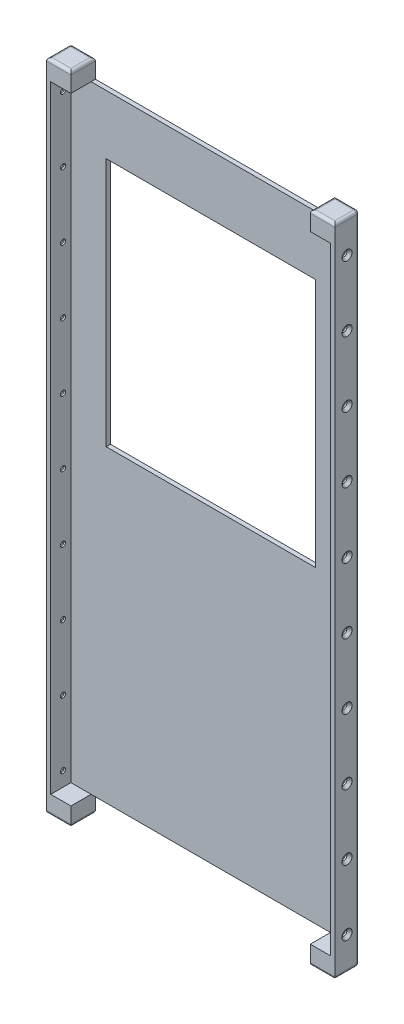
SolidWorks part; units mm, degrees
ref_plane "Front Plane" through (0, 0, 0) normal (0, 0, 1) x (1, 0, 0)
ref_plane "Top Plane" through (0, 0, 0) normal (0, 1, 0) x (1, 0, 0)
ref_plane "Right Plane" through (0, 0, 0) normal (1, 0, 0) x (0, 0, -1)
sketch "Sketch1" plane through (0, 0, 0) normal (0, 0, 1) x (1, 0, 0)
  line L0 (0, 107) -> (0, -107) construction
  line L1 (-41.5, -107) -> (41.5, -107)
  line L2 (-50, -107) -> (-50, 107)
  line L3 (-41.5, 107) -> (41.5, 107)
  line L4 (50, -107) -> (50, 107)
  line L5 (-50, -107) -> (50, 107) construction
  line L6 (-50, 107) -> (50, -107) construction
  line L7 (-50, 0) -> (50, 0) construction
  line L8 (-50, 107) -> (-50, 113.5)
  line L9 (-50, 113.5) -> (-41.5, 113.5)
  line L10 (-41.5, 107) -> (-41.5, 113.5)
  line L12 (50, 107) -> (50, 113.5)
  line L13 (50, 113.5) -> (41.5, 113.5)
  line L14 (41.5, 107) -> (41.5, 113.5)
  line L16 (50, -107) -> (50, -113.5)
  line L17 (50, -113.5) -> (41.5, -113.5)
  line L18 (41.5, -107) -> (41.5, -113.5)
  line L20 (-50, -107) -> (-50, -113.5)
  line L21 (-50, -113.5) -> (-41.5, -113.5)
  line L22 (-41.5, -107) -> (-41.5, -113.5)
  point P0 (0, 0)
  dimension "D1" = 100
  dimension "D2" = 227
  dimension "D3" = 8.5
  dimension "D4" = 6.5
extrude "Boss-Extrude1" add sketch "Sketch1" along normal blind 8.5
fillet "Fillet1" radius 1 18 edges at (41.5, -113.5, 4.25) (45.75, -113.5, 8.5) (50, -113.5, 4.25) (45.75, -113.5, 0) (-50, -113.5, 4.25) (-45.75, -113.5, 8.5) (-41.5, -113.5, 4.25) (-45.75, -113.5, 0) (-41.5, 113.5, 4.25) (-45.75, 113.5, 8.5) (-50, 113.5, 4.25) (-45.75, 113.5, 0) (41.5, 113.5, 4.25) (45.75, 113.5, 8.5) (50, 113.5, 4.25) (45.75, 113.5, 0) (-50, 0, 0) (50, 0, 0)
sketch "Sketch2" plane through (0, 0, 8.5) normal (0, 0, 1) x (1, 0, 0)
  line L1 (-41.5, 107) -> (41.5, 107)
  line L2 (-41.5, 107) -> (-41.5, -107)
  line L3 (-41.5, -107) -> (41.5, -107)
  line L4 (41.5, 107) -> (41.5, -107)
extrude "Cut-Extrude1" cut sketch "Sketch2" against normal blind 7
sketch "Sketch3" plane through (0, 0, 8.5) normal (0, 0, 1) x (1, 0, 0)
  line L0 (-50, 112.5) -> (-50, -112.5) construction
  line L1 (-48.5, 107) -> (48.5, 107)
  line L2 (-48.5, 107) -> (-48.5, -107)
  line L3 (-48.5, -107) -> (48.5, -107)
  line L4 (48.5, 107) -> (48.5, -107)
  line L5 (50, -112.5) -> (50, 112.5) construction
  line L6 (41.5, 107) -> (-41.5, 107) construction
  line L7 (-41.5, -107) -> (41.5, -107) construction
  dimension "D1" = 1.5
  dimension "D2" = 1.5
extrude "Cut-Extrude2" cut sketch "Sketch3" against normal up to surface (7 mm away) up to face at (0, 0, 1.5)
sketch "Sketch6" plane through (0, 0, 0) normal (0, 0, -1) x (-1, 0, 0)
  line L0 (0, 107) -> (0, -107) construction
  line L1 (-36.25, 86.5) -> (36.25, 86.5)
  line L2 (-36.25, 86.5) -> (-36.25, 0)
  line L3 (-36.25, 0) -> (36.25, 0)
  line L4 (36.25, 86.5) -> (36.25, 0)
  line L5 (-36.25, -27) -> (36.25, -27)
  line L6 (-36.25, -27) -> (-36.25, -113.5)
  line L7 (-36.25, -113.5) -> (36.25, -113.5)
  line L8 (36.25, -27) -> (36.25, -113.5)
  line L9 (-41.5, 107) -> (41.5, 107) construction
  line L10 (41.5, -107) -> (-41.5, -107) construction
  line L12 (-42.5, -113.5) -> (-49, -113.5) construction
  dimension "D1" = 72.5
  dimension "D2" = 86.5
  dimension "D3" = 27
  dimension "D4" = 86.5
extrude "Cut-Extrude3" cut sketch "Sketch6" against normal blind 10 contours L0 L1 L2 L3 | L1 L0 L3 L4
hole_wizard "CSK for #0 Flat Head Machine Screw1" positions "Sketch8" profile "Sketch7" countersink size "#0" standard "ANSI Inch"
sketch "Sketch8" plane through (50, 0, 0) normal (1, 0, 0) x (0, 0, -1)
  line L0 (-8.5, -112.5) -> (-8.5, 112.5) construction
  point P0 (-4.25, 102)
  point P15 (-4.25, 79.3333)
  point P16 (-4.25, 56.6667)
  point P17 (-4.25, 34)
  point P18 (-4.25, 11.3333)
  point P19 (-4.25, -11.3333)
  point P20 (-4.25, -34)
  point P21 (-4.25, -56.6667)
  point P22 (-4.25, -79.3333)
  point P23 (-4.25, -102)
  dimension "D1" = 4.25
  dimension "D2" = 5
  dimension "D4" = 5
  dimension "D3" = 10
sketch "Sketch7" plane through (50, 102, 4.25) normal (0, 1, 0) x (0, 0, -1)
  line L0 (0, 0) -> (0, 3.8362)
  line L1 (0, 3.8362) -> (0.889, 3.302)
  line L2 (0.889, 3.302) -> (0.889, 0.9699)
  line L3 (0.889, 0.9699) -> (1.7321, 0)
  line L5 (1.7321, 0) -> (0, 0)
  line L6 (-0.889, 0.9699) -> (-1.7321, 0) construction
  line L10 (0, 3.8362) -> (-0.889, 3.302) construction
  line L11 (0, -6.35) -> (0, 107.95) construction
  dimension "Hole Dia." = 1.778
  dimension "Hole Depth" = 3.302
  dimension "Near C'Sink Dia." = 3.4642
  dimension "Near C'Sink Angle" = 82
  dimension "Drill Angle" = 118
mirror "Mirror1" about plane through (0, 0, 0) normal (1, 0, 0) of "CSK for #0 Flat Head Machine Screw1"
